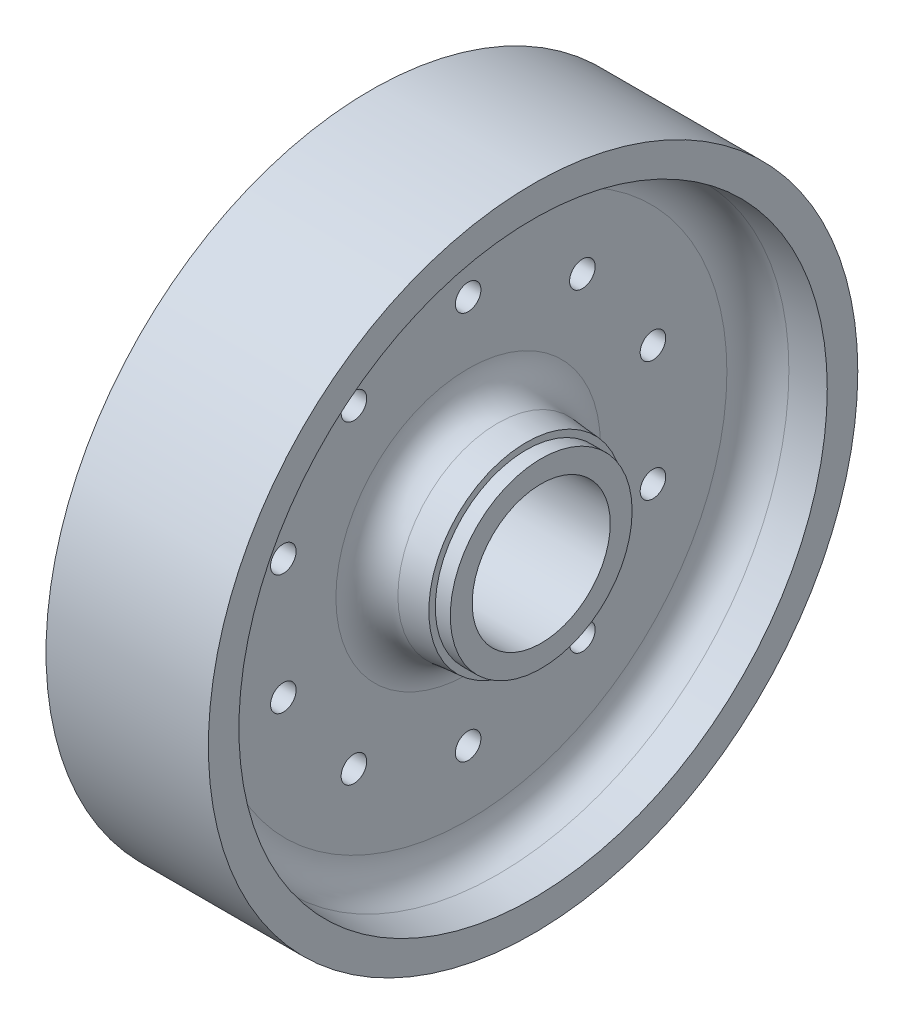
SolidWorks part; units mm, degrees
ref_plane "Plano frontal" through (0, 0, 0) normal (0, 0, 1) x (1, 0, 0)
ref_plane "Plano superior" through (0, 0, 0) normal (0, 1, 0) x (1, 0, 0)
ref_plane "Plano direito" through (0, 0, 0) normal (1, 0, 0) x (0, 0, -1)
sketch "Esboço1" plane through (0, 0, 0) normal (0, 0, 1) x (1, 0, 0)
  line L0 (-14.5288, 17.78) -> (-17.4625, 17.78)
  line L1 (-17.4625, 17.78) -> (-17.4625, 13.5001)
  line L2 (-17.4625, 13.5001) -> (17.4625, 13.5001)
  line L3 (17.4625, 13.5001) -> (17.4625, 17.78)
  line L4 (17.4625, 17.78) -> (14.5288, 17.78)
  line L5 (14.5288, 17.78) -> (14.5288, 19.05)
  line L6 (14.5288, 19.05) -> (8.9716, 19.5362)
  line L7 (3.175, 25.862) -> (3.175, 50.6012)
  line L8 (8.9716, 56.927) -> (15.875, 57.531)
  line L9 (15.875, 57.531) -> (15.875, 63.5)
  line L10 (15.875, 63.5) -> (-15.875, 63.5)
  line L11 (-15.875, 63.5) -> (-15.875, 57.531)
  line L12 (-15.875, 57.531) -> (-8.9716, 56.927)
  line L13 (-3.175, 50.6012) -> (-3.175, 25.862)
  line L14 (-8.9716, 19.5362) -> (-14.5288, 19.05)
  line L15 (-14.5288, 19.05) -> (-14.5288, 17.78)
  line L16 (-17.4625, 0) -> (17.4625, 0) construction
  arc A0 (8.9716, 19.5362) -> (3.175, 25.862) centre (9.525, 25.862) cw
  arc A1 (3.175, 50.6012) -> (8.9716, 56.927) centre (9.525, 50.6012) cw
  arc A2 (-8.9716, 56.927) -> (-3.175, 50.6012) centre (-9.525, 50.6012) cw
  arc A3 (-3.175, 25.862) -> (-8.9716, 19.5362) centre (-9.525, 25.862) cw
revolve "Revolução1" add sketch "Esboço1" angle 360 about L16
sketch "Esboço2" plane through (0, 0, 0) normal (1, 0, 0) x (0, 0, -1)
  circle A0 centre (0, 38) radius 2.5
  circle A1 centre (22.3358, 30.7426) radius 2.5
  circle A2 centre (36.1401, 11.7426) radius 2.5
  circle A3 centre (36.1401, -11.7426) radius 2.5
  circle A4 centre (22.3358, -30.7426) radius 2.5
  circle A5 centre (0, -38) radius 2.5
  circle A6 centre (-22.3358, -30.7426) radius 2.5
  circle A7 centre (-36.1401, -11.7426) radius 2.5
  circle A8 centre (-36.1401, 11.7426) radius 2.5
  circle A9 centre (-22.3358, 30.7426) radius 2.5
  point P15 (0, 0)
  dimension "D1" = 10
  dimension "D3" = 5
  dimension "D2" = 38
extrude "Corte-extrusão3" cut sketch "Esboço2" against normal through all both and the other way through all
